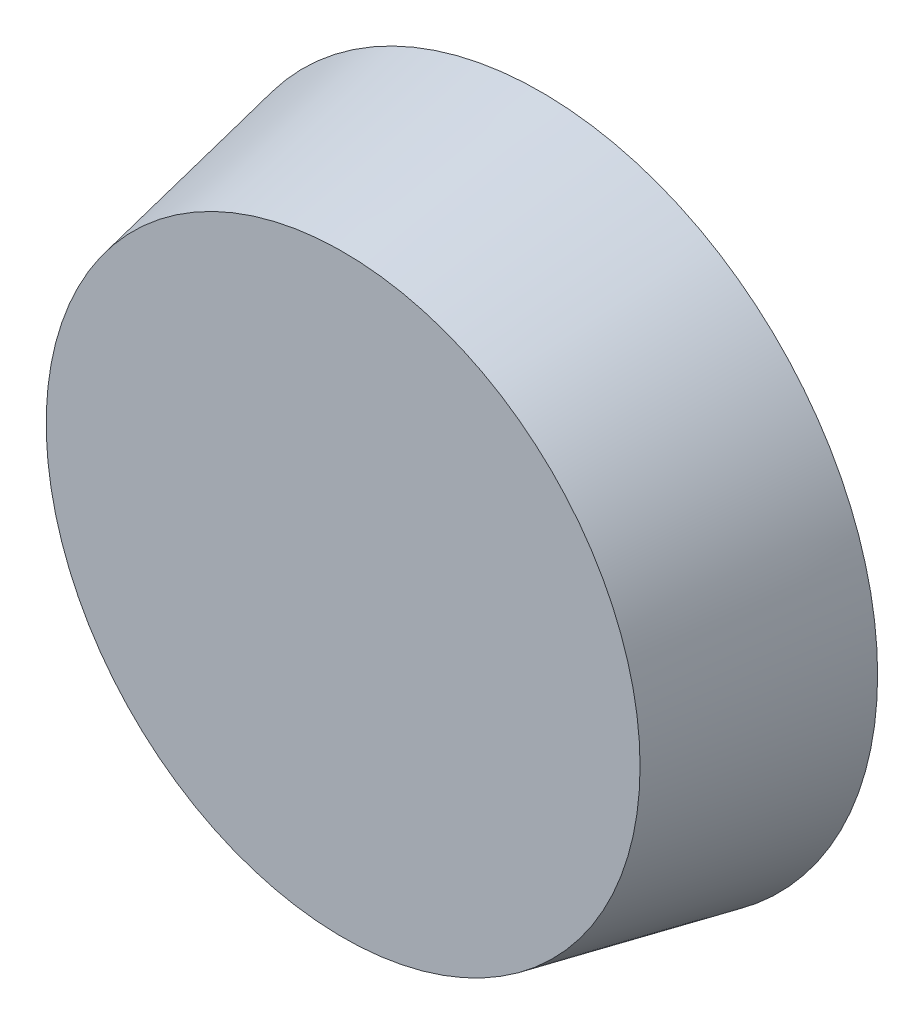
SolidWorks part; units mm, degrees
material "Silicon Rubber"
ref_plane "Front Plane" through (0, 0, 0) normal (0, 0, 1) x (1, 0, 0)
ref_plane "Top Plane" through (0, 0, 0) normal (0, 1, 0) x (1, 0, 0)
ref_plane "Right Plane" through (0, 0, 0) normal (1, 0, 0) x (0, 0, -1)
sketch "Sketch1" plane through (0, 0, 0) normal (0, 0, 1) x (1, 0, 0)
  circle A0 centre (0, 0) radius 53.975
  dimension "D1" = 107.95
ref_plane "Plane1" through (0, 0, 31.75) normal (0, 0, 1) x (1, 0, 0)
sketch "Sketch2" plane through (0, 0, 31.75) normal (0, 0, 1) x (1, 0, 0)
  circle A0 centre (0, 0) radius 47.625
  dimension "D1" = 95.25
loft "Loft1" add profiles "Sketch1", "Sketch2"
